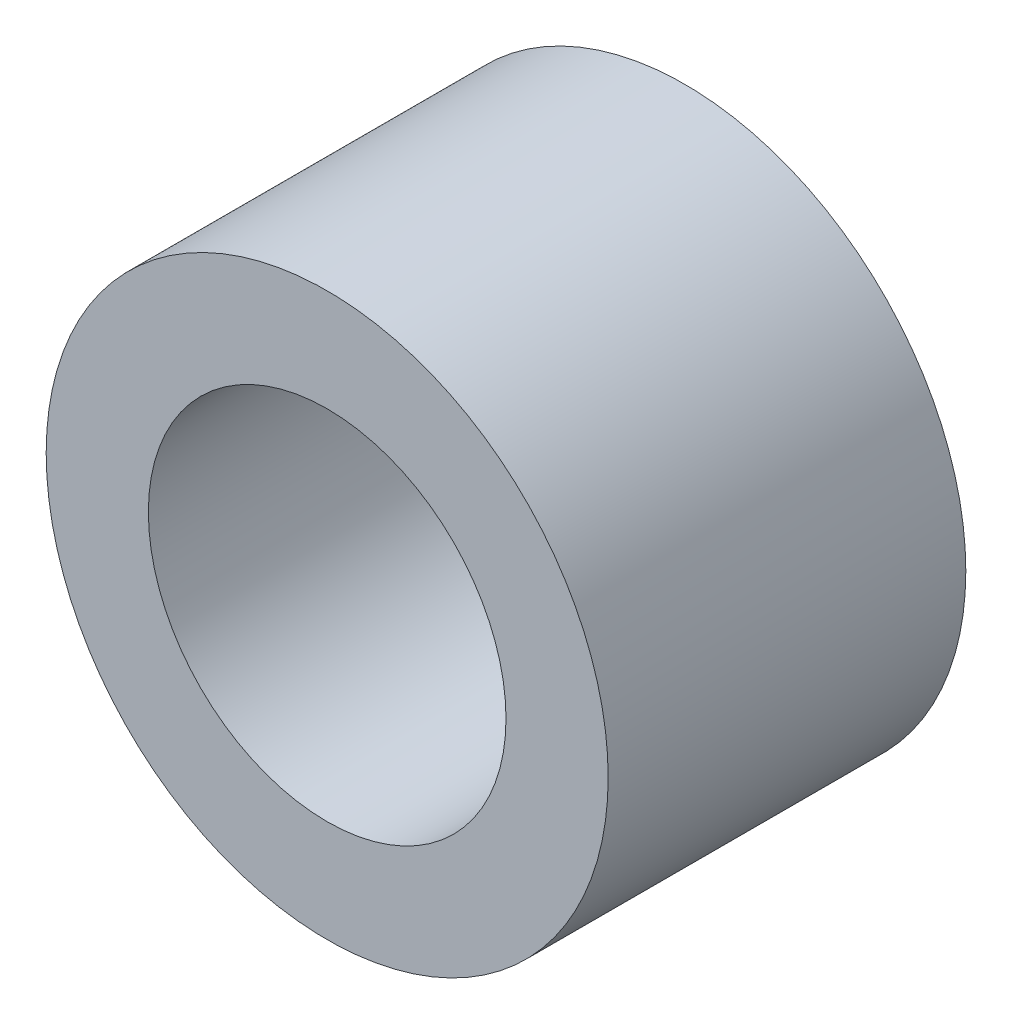
SolidWorks part; units mm, degrees
material "ABS"
ref_plane "前视基准面" through (0, 0, 0) normal (0, 0, 1) x (1, 0, 0)
ref_plane "上视基准面" through (0, 0, 0) normal (0, 1, 0) x (1, 0, 0)
ref_plane "右视基准面" through (0, 0, 0) normal (1, 0, 0) x (0, 0, -1)
sketch "草图1" plane through (0, 0, 0) normal (0, 0, 1) x (1, 0, 0)
  circle A0 centre (0, 0) radius 2.75
  circle A1 centre (0, 0) radius 1.75
  dimension "D1" = 3.5
  dimension "D2" = 5.5
extrude "凸台-拉伸1" add sketch "草图1" along normal blind 3.5
